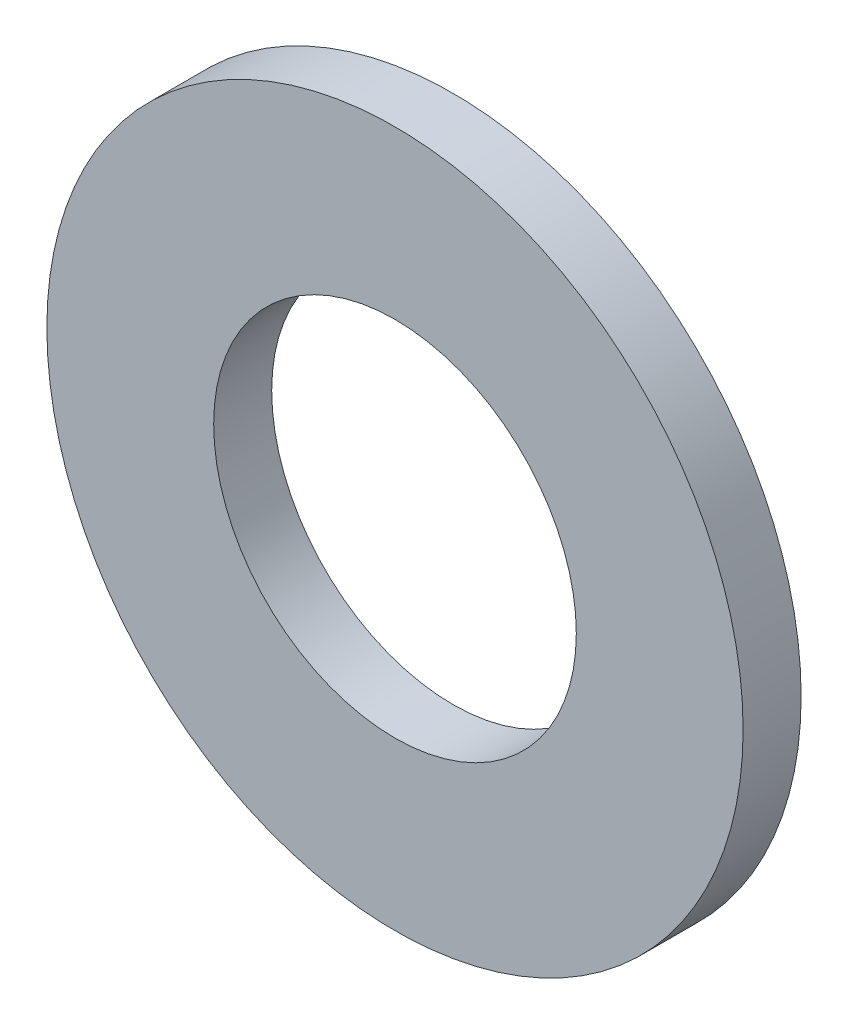
SolidWorks part; units mm, degrees
ref_plane "Front Plane" through (0, 0, 0) normal (0, 0, 1) x (1, 0, 0)
ref_plane "Top Plane" through (0, 0, 0) normal (0, 1, 0) x (1, 0, 0)
ref_plane "Right Plane" through (0, 0, 0) normal (1, 0, 0) x (0, 0, -1)
sketch "Sketch2" plane through (0, 0, 0) normal (0, 0, 1) x (1, 0, 0)
  circle A0 centre (0, 0) radius 6
  circle A1 centre (0, 0) radius 3.125
  dimension "D1" = 12
  dimension "D2" = 6.25
extrude "Boss-Extrude1" add sketch "Sketch2" along normal mid plane 1
